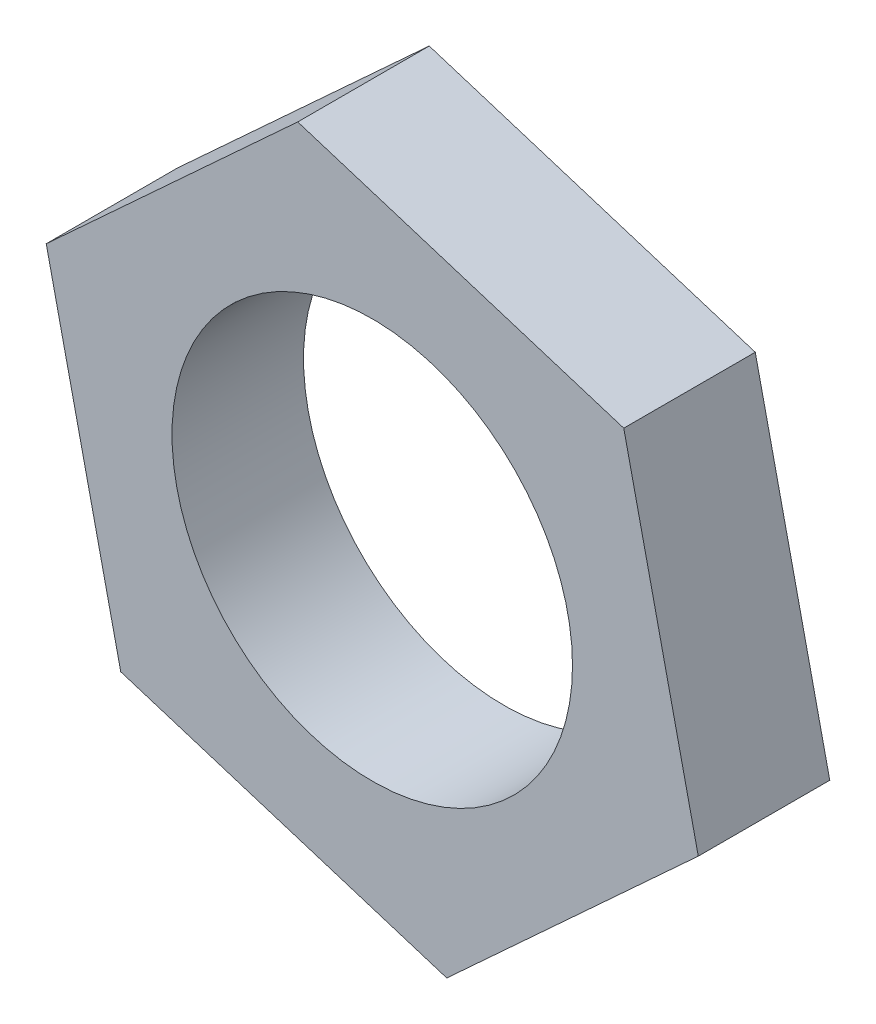
SolidWorks part; units mm, degrees
ref_plane "前视基准面" through (0, 0, 0) normal (0, 0, 1) x (1, 0, 0)
ref_plane "上视基准面" through (0, 0, 0) normal (0, 1, 0) x (1, 0, 0)
ref_plane "右视基准面" through (0, 0, 0) normal (1, 0, 0) x (0, 0, -1)
sketch "草图1" plane through (0, 0, 0) normal (0, 0, 1) x (1, 0, 0)
  line L1 (4.2075, 3.8687) -> (-1.2466, 5.5782)
  line L2 (-1.2466, 5.5782) -> (-5.4541, 1.7095)
  line L3 (-5.4541, 1.7095) -> (-4.2075, -3.8687)
  line L4 (-4.2075, -3.8687) -> (1.2466, -5.5782)
  line L5 (1.2466, -5.5782) -> (5.4541, -1.7095)
  line L6 (5.4541, -1.7095) -> (4.2075, 3.8687)
  circle A0 centre (0, 0) radius 3.35
  circle A1 centre (0, 0) radius 4.95 construction
  dimension "D2" = 6.7
  dimension "D1" = 9.9
extrude "凸台-拉伸1" add sketch "草图1" along normal blind 2.2
cosmetic thread "装饰螺纹线1" parameters "D2"=8
